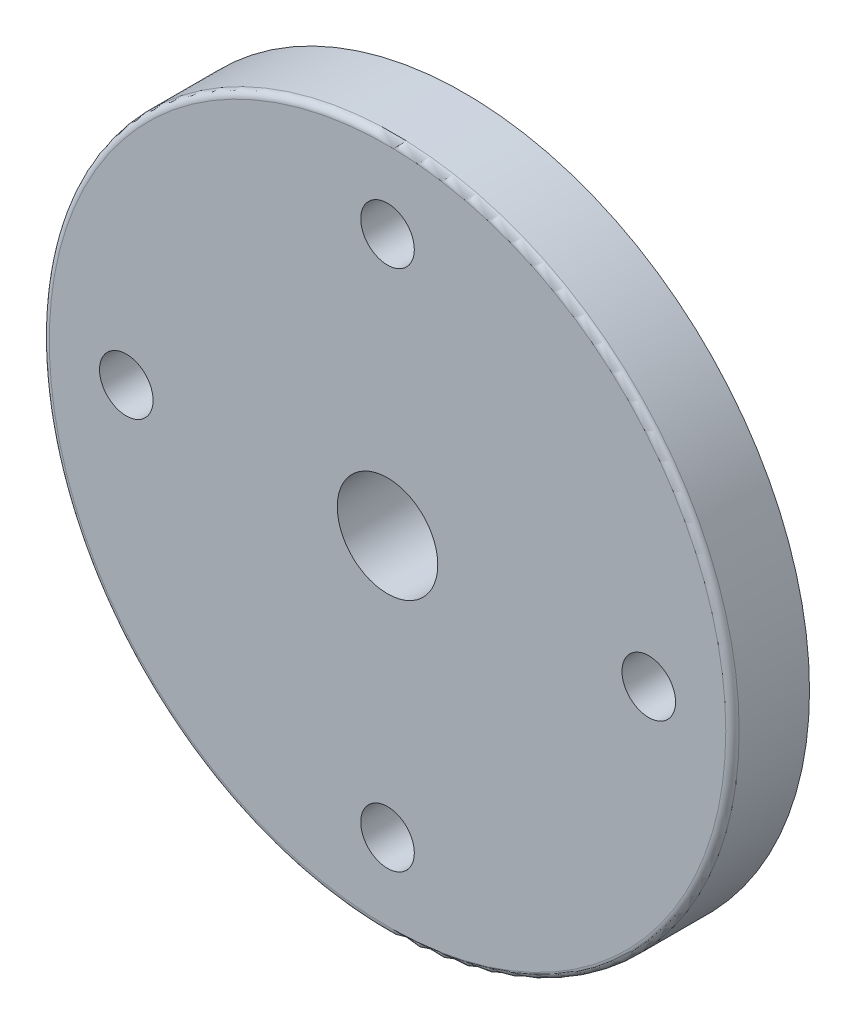
SolidWorks part; units mm, degrees
material "PLA_Circular_Horn"
ref_plane "Front Plane" through (0, 0, 0) normal (0, 0, 1) x (1, 0, 0)
ref_plane "Top Plane" through (0, 0, 0) normal (0, 1, 0) x (1, 0, 0)
ref_plane "Right Plane" through (0, 0, 0) normal (1, 0, 0) x (0, 0, -1)
ref_plane "Plane1" through (0, 0, -2.5) normal (0, 0, -1) x (-1, 0, 0)
sketch "Sketch1" plane through (0, 0, -2.5) normal (0, 0, -1) x (-1, 0, 0)
  circle A0 centre (0, 0) radius 10.3
  dimension "D1" = 20.6
extrude "Boss-Extrude1" add sketch "Sketch1" against normal blind 2.3
sketch "Sketch2" plane through (0, 0, -2.5) normal (0, 0, -1) x (-1, 0, 0)
  circle A0 centre (0, 0) radius 4.375
  dimension "D1" = 8.75
extrude "Boss-Extrude2" add sketch "Sketch2" along normal blind 3.2
sketch "Sketch3" plane through (0, 0, -5.7) normal (0, 0, -1) x (-1, 0, 0)
  circle A0 centre (0, 0) radius 3
  dimension "D1" = 6
extrude "Cut-Extrude1" cut sketch "Sketch3" against normal blind 2.75
sketch "Sketch4" plane through (0, 0, -0.2) normal (0, 0, 1) x (1, 0, 0)
  circle A0 centre (0, 0) radius 1.5
extrude "Cut-Extrude2" cut sketch "Sketch4" against normal through all
sketch "Sketch12" plane through (0, 0, -2.5) normal (0, 0, -1) x (-1, 0, 0)
  circle A0 centre (0, 7.8) radius 0.8
  circle A1 centre (0, 0) radius 7.8 construction
  circle A2 centre (7.8, 0) radius 0.8
  circle A3 centre (0, -7.8) radius 0.8
  circle A4 centre (-7.8, 0) radius 0.8
  point P14 (0, 0)
  dimension "D1" = 1.6
  dimension "D2" = 15.6
  dimension "D3" = 4
extrude "Cut-Extrude10" cut sketch "Sketch12" against normal through all
fillet "Fillet2" radius 0.2 1 edges at (10.3, 0, -0.2)
fillet "Fillet3" radius 0.3 1 edges at (-4.375, 0, -5.7)
